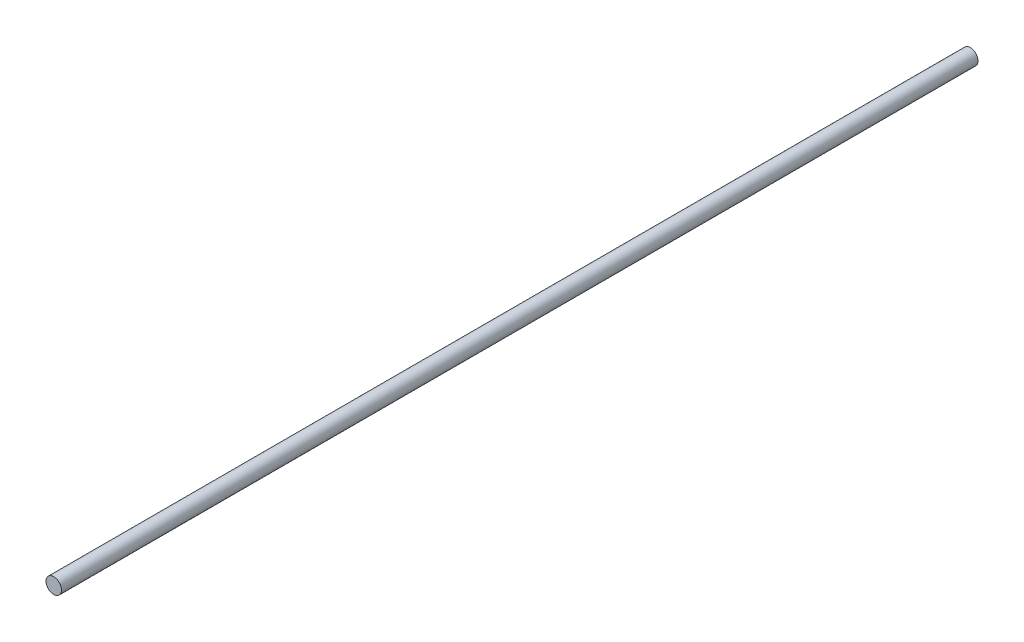
SolidWorks part; units mm, degrees
ref_plane "Płaszczyzna przednia" through (0, 0, 0) normal (0, 0, 1) x (1, 0, 0)
ref_plane "Płaszczyzna górna" through (0, 0, 0) normal (0, 1, 0) x (1, 0, 0)
ref_plane "Płaszczyzna prawa" through (0, 0, 0) normal (1, 0, 0) x (0, 0, -1)
sketch "Szkic1" plane through (0, 0, 0) normal (0, 0, 1) x (1, 0, 0)
  circle A0 centre (0, 0) radius 4
extrude "Dodanie-wyciągnięcie1" add sketch "Szkic1" along normal blind 475
